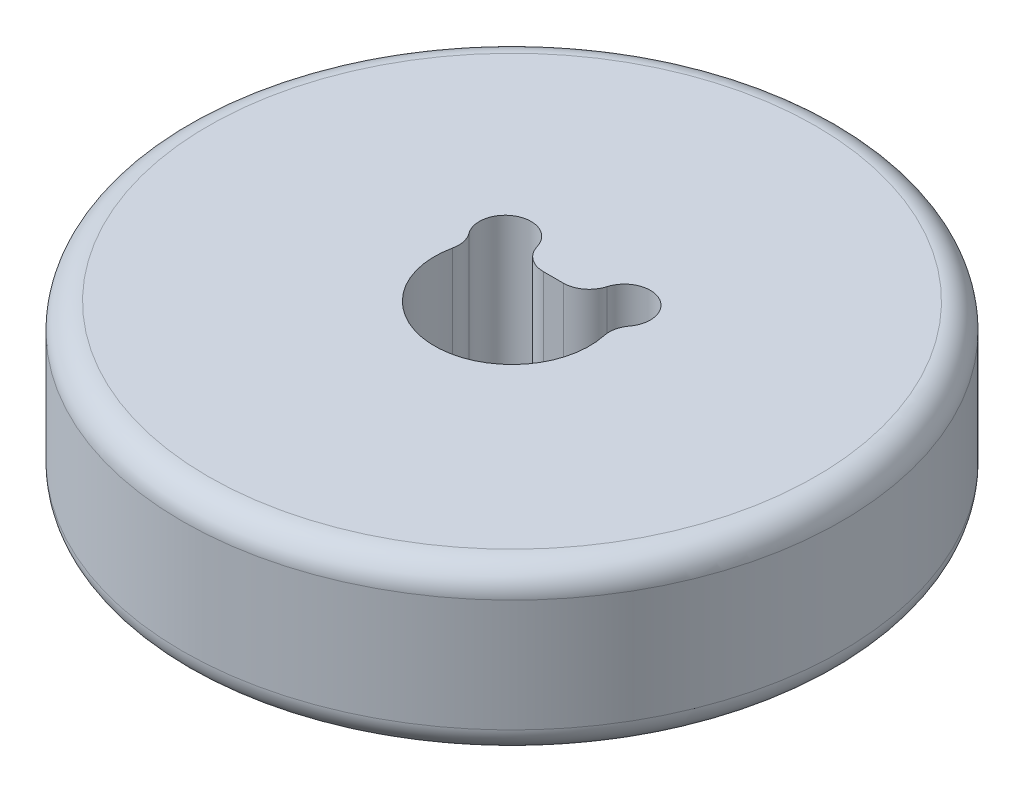
SolidWorks part; units mm, degrees
ref_plane "Front Plane" through (0, 0, 0) normal (0, 0, 1) x (1, 0, 0)
ref_plane "Top Plane" through (0, 0, 0) normal (0, 1, 0) x (1, 0, 0)
ref_plane "Right Plane" through (0, 0, 0) normal (1, 0, 0) x (0, 0, -1)
sketch "Sketch1" plane through (0, 0, 0) normal (0, 1, 0) x (1, 0, 0)
  line L4 (1.411, 1.6) -> (-1.411, 1.6)
  arc A0 (-2.7682, 1.1563) -> (2.7682, 1.1563) centre (0, 0) ccw
  circle A1 centre (0, 0) radius 12.75
  arc A2 (-1.411, 1.6) -> (-2.7682, 1.1563) centre (-2.3072, 2.0437) ccw
  arc A3 (2.7682, 1.1563) -> (1.411, 1.6) centre (2.3072, 2.0437) ccw
  dimension "D1" = 6
  dimension "D2" = 25.5
  dimension "D3" = 2
  dimension "D4" = 1.6
extrude "Boss-Extrude1" add sketch "Sketch1" along normal blind 6.35
fillet "Fillet1" radius 1 4 edges at (2.7682, 3.175, -1.1563) (1.411, 3.175, -1.6) (-1.411, 3.175, -1.6) (-2.7682, 3.175, -1.1563)
fillet "Fillet2" radius 1 2 edges at (0, 6.35, 12.75) (0, 0, 12.75)
